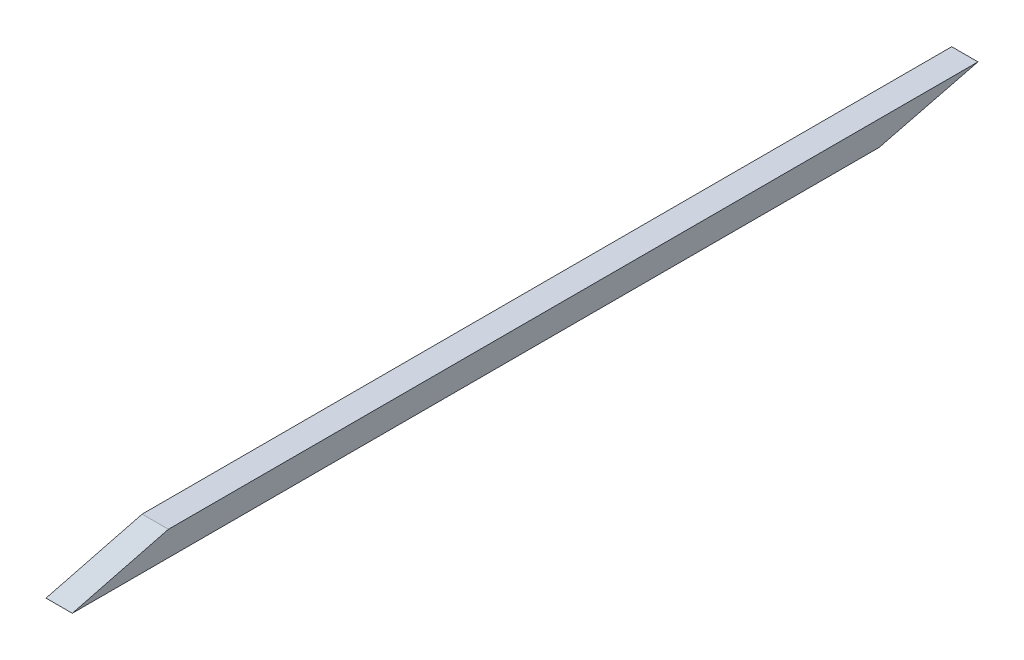
SolidWorks part; units mm, degrees
ref_plane "Front Plane" through (0, 0, 0) normal (0, 0, 1) x (1, 0, 0)
ref_plane "Top Plane" through (0, 0, 0) normal (0, 1, 0) x (1, 0, 0)
ref_plane "Right Plane" through (0, 0, 0) normal (1, 0, 0) x (0, 0, -1)
sketch "Sketch1" plane through (0, 0, 0) normal (0, 0, 1) x (1, 0, 0)
  line L1 (-29.1914, 29.8295) -> (20.8086, 29.8295)
  line L2 (-29.1914, 29.8295) -> (-29.1914, -17.1705)
  line L3 (-29.1914, -17.1705) -> (20.8086, -17.1705)
  line L4 (20.8086, 29.8295) -> (20.8086, -17.1705)
  dimension "D1" = 50
  dimension "D2" = 47
extrude "Boss-Extrude1" add sketch "Sketch1" along normal blind 1724.16
sketch "Sketch2" plane through (20.8086, 0, 0) normal (1, 0, 0) x (0, 0, -1)
  line L0 (-1724.16, -17.1705) -> (-1541.118, 29.8295)
  line L1 (-1724.16, 29.8295) -> (0, 29.8295) construction
  line L2 (-1724.16, -17.1705) -> (-95.0092, 401.1494) construction
  line L3 (-1541.118, 29.8295) -> (-1724.16, 29.8295)
  line L4 (-1724.16, 29.8295) -> (-1724.16, -17.1705)
  line L5 (0, 29.8295) -> (0, -17.1705)
  line L6 (0, -17.1705) -> (-188.1966, -17.1705)
  line L7 (-1724.16, -17.1705) -> (0, -17.1705) construction
  line L8 (-1629.1551, -387.1679) -> (-0.0043, 31.152) construction
  line L9 (0, 29.8295) -> (-188.1966, -17.1705)
extrude "Cut-Extrude1" cut sketch "Sketch2" against normal blind 50
